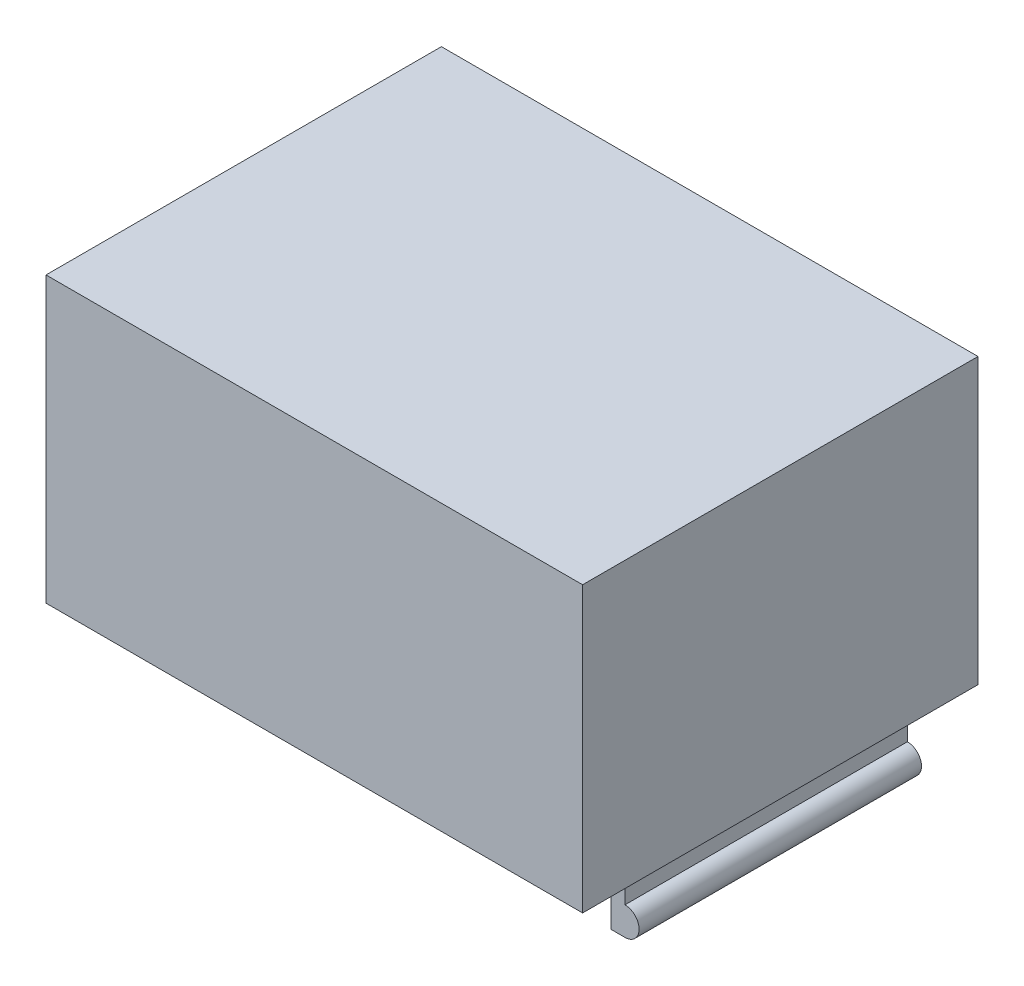
SolidWorks part; units mm, degrees
ref_plane "Front Plane" through (0, 0, 0) normal (0, 0, 1) x (1, 0, 0)
ref_plane "Top Plane" through (0, 0, 0) normal (0, 1, 0) x (1, 0, 0)
ref_plane "Right Plane" through (0, 0, 0) normal (1, 0, 0) x (0, 0, -1)
sketch "Sketch1" plane through (0, 0, 0) normal (0, 0, 1) x (1, 0, 0)
  line L1 (0, 0) -> (48.26, 0)
  line L2 (0, 0) -> (0, -25.5651)
  line L3 (0, -25.5651) -> (48.26, -25.5651)
  line L4 (48.26, 0) -> (48.26, -25.5651)
  dimension "D1" = 25.5651
  dimension "D2" = 48.26
extrude "Boss-Extrude1" add sketch "Sketch1" along normal mid plane 35.56 contours L1 L4 L3 L2
shell "Shell1" thickness 2.54
sketch "Sketch2" plane through (0, -2.54, 0) normal (0, -1, 0) x (1, 0, 0)
  circle A0 centre (27.94, 0) radius 3.175
  point P4 (0, 0)
  point P6 (5.7877, -2.5861)
  dimension "D1" = 27.94
  dimension "D2" = 6.35
extrude "Boss-Extrude2" add sketch "Sketch2" along normal blind 25.4
sketch "Sketch3" plane through (0, 0, 0) normal (0, 0, 1) x (1, 0, 0)
  line L0 (0, -25.5651) -> (48.26, -25.5651) construction
  line L1 (1.27, -25.5651) -> (2.54, -25.5651)
  line L3 (1.27, -30.6451) -> (2.54, -30.6451)
  line L4 (2.54, -25.5651) -> (2.54, -30.6451)
  line L5 (1.27, -28.1051) -> (1.27, -25.5651)
  line L6 (0, 0) -> (0, -25.5651) construction
  line L7 (45.72, -25.5651) -> (45.72, -30.6451)
  line L8 (45.72, -30.6451) -> (46.99, -30.6451)
  line L9 (46.99, -28.1051) -> (46.99, -25.5651)
  line L10 (46.99, -25.5651) -> (45.72, -25.5651)
  line L11 (48.26, 0) -> (48.26, -25.5651) construction
  arc A0 (1.27, -30.6451) -> (1.27, -28.1051) centre (1.27, -29.3751) cw
  arc A1 (46.99, -30.6451) -> (46.99, -28.1051) centre (46.99, -29.3751) ccw
  point P8 (1.27, -26.8351)
  dimension "D3" = 1.27
  dimension "D1" = 1.27
  dimension "D2" = 1.27
  dimension "D4" = 5.08
  dimension "D5" = 2.54
  dimension "D6" = 1.27
  dimension "D7" = 1.27
  dimension "D8" = 5.08
  dimension "D9" = 2.54
extrude "Boss-Extrude3" add sketch "Sketch3" along normal mid plane 25.4
